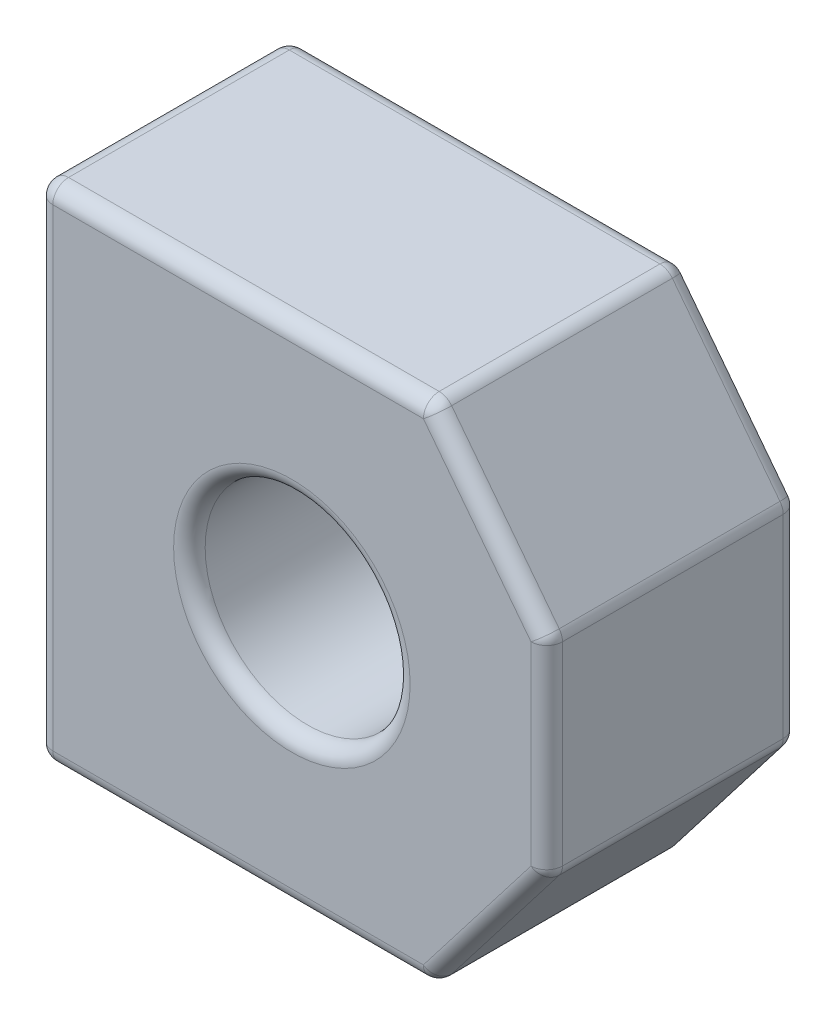
SolidWorks part; units mm, degrees
ref_plane "Front Plane" through (0, 0, 0) normal (0, 0, 1) x (1, 0, 0)
ref_plane "Top Plane" through (0, 0, 0) normal (0, 1, 0) x (1, 0, 0)
ref_plane "Right Plane" through (0, 0, 0) normal (1, 0, 0) x (0, 0, -1)
sketch "Sketch3" plane through (0, 0, 0) normal (0, 0, 1) x (1, 0, 0)
  line L0 (0, 0) -> (0, -32)
  line L1 (0, -32) -> (25, -32)
  line L2 (25, -32) -> (32.3314, -22.5)
  line L3 (32.3314, -22.5) -> (32.3314, -9.5)
  line L4 (32.3314, -9.5) -> (25, 0)
  line L5 (25, 0) -> (0, 0)
  point P7 (32.3314, -16)
  point P8 (0, -16)
  dimension "D1" = 12
  dimension "D2" = 12
  dimension "D3" = 32
  dimension "D4" = 13
  dimension "D5" = 25
extrude "Boss-Extrude1" add sketch "Sketch3" along normal blind 16
sketch "Sketch4" plane through (0, 0, 16) normal (0, 0, 1) x (1, 0, 0)
  line L0 (0, 0) -> (0, -32) construction
  line L1 (0, -16) -> (32.3314, -16) construction
  line L2 (32.3314, -22.5) -> (32.3314, -9.5) construction
  circle A0 centre (16.1657, -16) radius 6.5
  point P6 (0, -16)
  point P11 (16.1657, -16)
  dimension "D1" = 13
extrude "Cut-Extrude1" cut sketch "Sketch4" against normal blind 11
sketch "Sketch5" plane through (0, 0, 5) normal (0, 0, 1) x (1, 0, 0)
  circle A0 centre (16.1657, -16) radius 3.45
  circle A1 centre (16.1657, -16) radius 6.5
  circle A2 centre (16.1657, -16) radius 6.5
  dimension "D2" = 6.9
  dimension "D1" = 0
extrude "Cut-Extrude2" cut sketch "Sketch5" against normal blind 11 contours A0
fillet "Fillet1" radius 1 20 edges at (22.6657, -16, 5) (28.6657, -4.75, 0) (32.3314, -9.5, 8) (32.3314, -16, 0) (12.5, -32, 0) (25, -32, 8) (32.3314, -22.5, 8) (28.6657, -27.25, 0) (0, -32, 8) (0, -16, 0) (28.6657, -4.75, 16) (32.3314, -16, 16) (28.6657, -27.25, 16) (12.5, -32, 16) (0, -16, 16) (22.6657, -16, 16) (25, 0, 8) (12.5, 0, 16) (0, 0, 8) (12.5, 0, 0)
